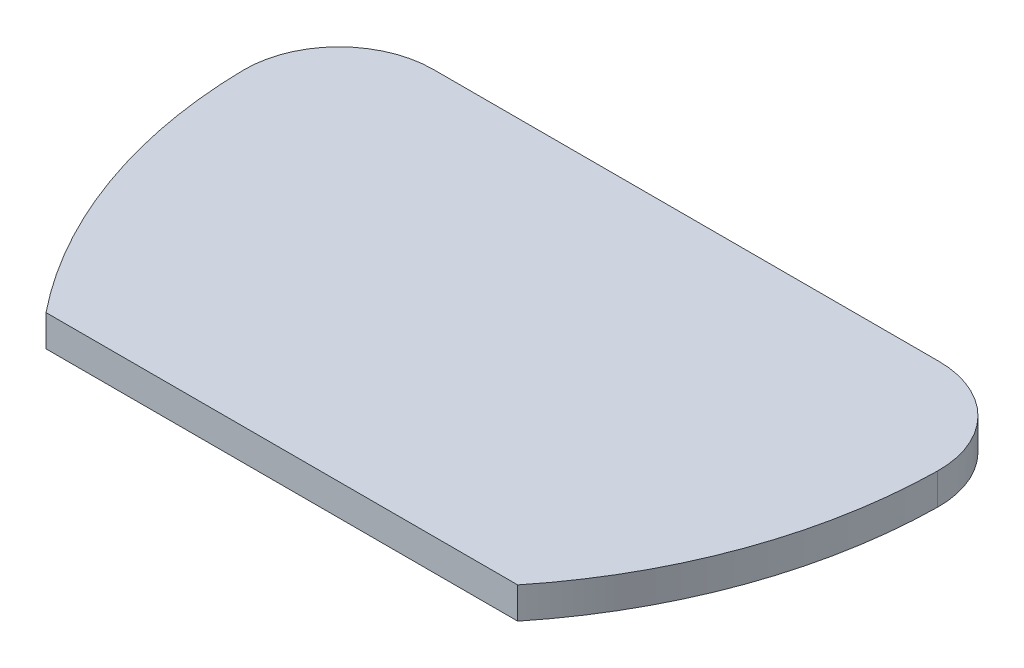
SolidWorks part; units mm, degrees
ref_plane "Front Plane" through (0, 0, 0) normal (0, 0, 1) x (1, 0, 0)
ref_plane "Top Plane" through (0, 0, 0) normal (0, 1, 0) x (1, 0, 0)
ref_plane "Right Plane" through (0, 0, 0) normal (1, 0, 0) x (0, 0, -1)
sketch "Sketch12" plane through (0, 0, 0) normal (0, 1, 0) x (1, 0, 0)
  line L0 (47.6593, 0) -> (-47.6593, 0)
  line L1 (51.0968, 81.6849) -> (-51.0968, 81.6849)
  line L7 (0, 0) -> (0, 81.6849) construction
  arc A0 (47.6593, 0) -> (70.1446, 62.3453) centre (-31.8297, 63.8957) ccw
  arc A1 (-47.6593, 0) -> (-70.1446, 62.3453) centre (31.8297, 63.8957) cw
  arc A2 (70.1446, 62.3453) -> (51.0968, 81.6849) centre (51.0968, 62.6349) ccw
  arc A3 (-70.1446, 62.3453) -> (-51.0968, 81.6849) centre (-51.0968, 62.6349) cw
  point P0 (0, 0)
  point P12 (68.5929, 81.6849)
  point P15 (-68.5929, 81.6849)
  dimension "D1" = 19.05
extrude "Extrude3" add sketch "Sketch12" against normal blind 6.35
sketch "Sketch1" plane through (0, 0, 0) normal (0, 0, 1) x (1, 0, 0)
  line L1 (47.6593, -6.35) -> (70.1446, -6.35) construction
  line L2 (57.8193, -5.6515) -> (57.8193, 2.794)
  line L3 (55.5333, 5.08) -> (49.9453, 5.08)
  line L4 (47.6593, 2.794) -> (47.6593, 0)
  line L5 (47.6593, 0) -> (47.6593, -7.9375)
  line L6 (47.6593, -7.9375) -> (55.5333, -7.9375)
  arc A0 (49.9453, 5.08) -> (47.6593, 2.794) centre (49.9453, 2.794) ccw
  arc A1 (57.8193, 2.794) -> (55.5333, 5.08) centre (55.5333, 2.794) ccw
  arc A2 (57.8193, -5.6515) -> (55.5333, -7.9375) centre (55.5333, -5.6515) cw
  point P15 (57.8193, -6.35)
  dimension "D1" = 2.286
  dimension "D2" = 2.286
  dimension "D3" = 10.16
sketch "Sketch2" plane through (0, 0, 0) normal (1, 0, 0) x (0, 0, -1)
  line L1 (96.9249, -5.6515) -> (96.9249, 5.0898)
  line L2 (81.6849, -7.9375) -> (94.6389, -7.9375)
  line L3 (81.6849, 5.0898) -> (81.6849, -7.9375)
  arc A0 (95.8665, 7.4564) -> (82.7434, 7.4564) centre (89.3049, 0.1197) ccw
  arc A1 (82.7434, 7.4564) -> (81.6849, 5.0898) centre (84.8599, 5.0898) ccw
  arc A2 (96.9249, 5.0898) -> (95.8665, 7.4564) centre (93.7499, 5.0898) ccw
  arc A3 (96.9249, -5.6515) -> (94.6389, -7.9375) centre (94.6389, -5.6515) cw
  point P10 (96.9249, 6.35)
  point P13 (96.9249, -6.35)
  dimension "D3" = 3.175
  dimension "D4" = 2.286
  dimension "D2" = 12.7
sketch "Sketch3" plane through (0, 0, 0) normal (0, 0, 1) x (1, 0, 0)
  line L2 (-57.8193, -5.6515) -> (-57.8193, 2.794)
  line L3 (-55.5333, 5.08) -> (-49.9453, 5.08)
  line L4 (-47.6593, 2.794) -> (-47.6593, -7.9375)
  line L5 (-47.6593, -7.9375) -> (-55.5333, -7.9375)
  arc A0 (-57.8193, 2.794) -> (-55.5333, 5.08) centre (-55.5333, 2.794) cw
  arc A1 (-49.9453, 5.08) -> (-47.6593, 2.794) centre (-49.9453, 2.794) cw
  arc A2 (-55.5333, -7.9375) -> (-57.8193, -5.6515) centre (-55.5333, -5.6515) cw
  point P5 (-57.8193, 5.08)
  point P12 (-57.8193, -6.35)
  dimension "D3" = 2.286
  dimension "D4" = 2.286
  dimension "D2" = 11.43
sketch "Sketch4" plane through (0, 0, 0) normal (0, 1, 0) x (1, 0, 0)
  line L0 (51.0968, 81.6849) -> (-51.0968, 81.6849) construction
  line L1 (51.0968, 81.6849) -> (-51.0968, 81.6849)
  arc A0 (47.6593, 0) -> (70.1446, 62.3453) centre (-31.8297, 63.8957) ccw construction
  arc A1 (47.6593, 0) -> (70.1446, 62.3453) centre (-31.8297, 63.8957) ccw
  arc A2 (70.1446, 62.3453) -> (51.0968, 81.6849) centre (51.0968, 62.6349) ccw construction
  arc A3 (70.1446, 62.3453) -> (51.0968, 81.6849) centre (51.0968, 62.6349) ccw
  arc A4 (-51.0968, 81.6849) -> (-70.1446, 62.3453) centre (-51.0968, 62.6349) ccw construction
  arc A5 (-51.0968, 81.6849) -> (-70.1446, 62.3453) centre (-51.0968, 62.6349) ccw
  arc A6 (-70.1446, 62.3453) -> (-47.6593, 0) centre (31.8297, 63.8957) ccw construction
  arc A7 (-70.1446, 62.3453) -> (-47.6593, 0) centre (31.8297, 63.8957) ccw
